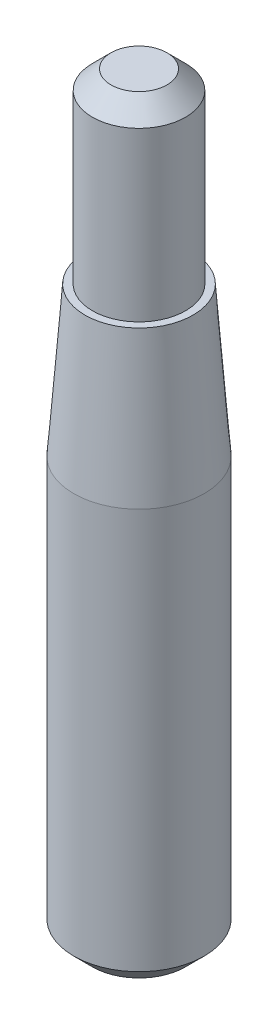
SolidWorks part; units mm, degrees
ref_plane "Front Plane" through (0, 0, 0) normal (0, 0, 1) x (1, 0, 0)
ref_plane "Top Plane" through (0, 0, 0) normal (0, 1, 0) x (1, 0, 0)
ref_plane "Right Plane" through (0, 0, 0) normal (1, 0, 0) x (0, 0, -1)
sketch "Sketch2" plane through (0, 0, 0) normal (0, 1, 0) x (1, 0, 0)
  circle A0 centre (0, 0) radius 7
  dimension "D1" = 14
extrude "Boss-Extrude1" add sketch "Sketch2" along normal blind 45
sketch "Sketch3" plane through (0, 45, 0) normal (0, 1, 0) x (1, 0, 0)
  circle A1 centre (0, 0) radius 7
  circle A2 centre (0, 0) radius 7
  dimension "D1" = 0
extrude "Boss-Extrude2" add sketch "Sketch3" along normal blind 16 draft 4.289
sketch "Sketch4" plane through (0, 61, 0) normal (0, 1, 0) x (1, 0, 0)
  circle A0 centre (0, 0) radius 5
  dimension "D1" = 10
extrude "Boss-Extrude3" add sketch "Sketch4" along normal blind 20
cosmetic thread "Cosmetic Thread2" parameters "D1"=16, "D2"=8.891
chamfer "Chamfer1" distance 2 angle 45 2 edges at (0, 0, 7) (0, 81, 5)
